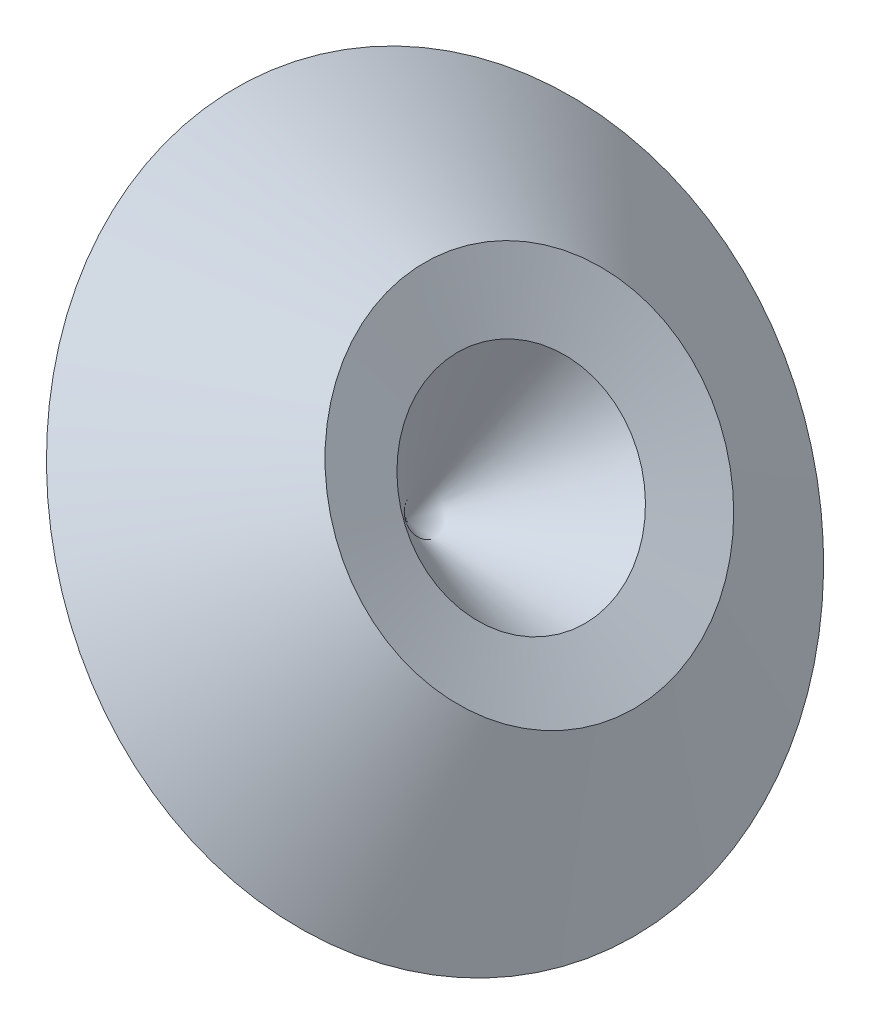
SolidWorks part; units mm, degrees
ref_plane "Front Plane" through (0, 0, 0) normal (0, 0, 1) x (1, 0, 0)
ref_plane "Top Plane" through (0, 0, 0) normal (0, 1, 0) x (1, 0, 0)
ref_plane "Right Plane" through (0, 0, 0) normal (1, 0, 0) x (0, 0, -1)
sketch "Sketch1" plane through (0, 0, 0) normal (0, 0, 1) x (1, 0, 0)
  line L0 (0, 0) -> (38.9541, 28.9169)
  line L1 (38.9541, 28.9169) -> (94.5801, 28.9169)
  line L2 (94.5801, 28.9169) -> (109.8466, 13.6504)
  line L3 (109.8466, 13.6504) -> (109.8466, -47.5636)
  line L4 (109.8466, -47.5636) -> (95.227, -47.5636)
  line L5 (95.227, -47.5636) -> (95.227, -17.0836)
  line L6 (95.227, -17.0836) -> (63.9203, -11.3666)
  line L7 (63.9203, -11.3666) -> (52.4256, -22.8613)
  line L8 (52.4256, -22.8613) -> (52.4256, -34.29)
  line L9 (52.4256, -34.29) -> (0, -34.29)
  line L10 (0, -34.29) -> (0, 0)
  dimension "D1" = 48.514
  dimension "D2" = 55.626
  dimension "D3" = 21.59
  dimension "D4" = 61.214
  dimension "D5" = 30.48
  dimension "D6" = 31.3067
  dimension "D7" = 16.256
  dimension "D8" = 11.4287
  dimension "D9" = 52.4256
  dimension "D10" = 34.29
revolve "Revolve1" add sketch "Sketch1" angle 360 about L0
